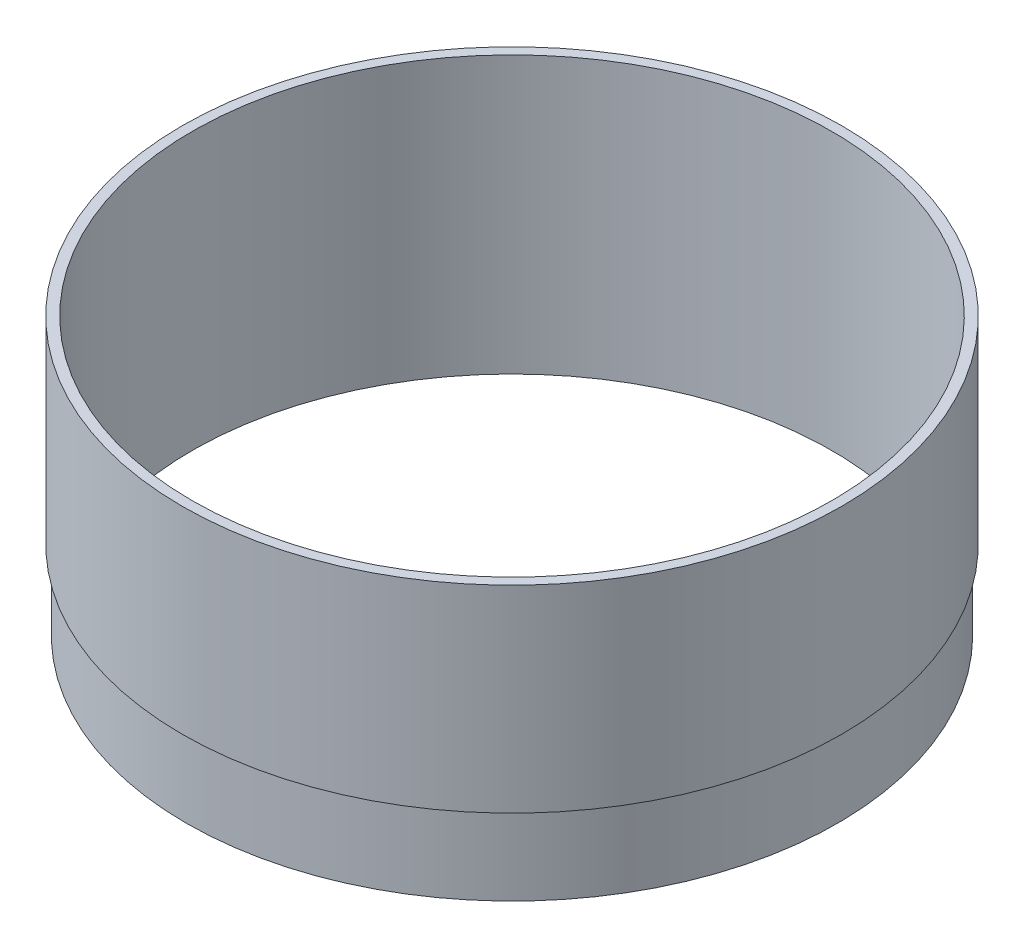
SolidWorks part; units mm, degrees
ref_plane "Front Plane" through (0, 0, 0) normal (0, 0, 1) x (1, 0, 0)
ref_plane "Top Plane" through (0, 0, 0) normal (0, 1, 0) x (1, 0, 0)
ref_plane "Right Plane" through (0, 0, 0) normal (1, 0, 0) x (0, 0, -1)
sketch "Sketch2" plane through (0, 0, 0) normal (0, 1, 0) x (1, 0, 0)
  circle A0 centre (0, 0) radius 16.5
  circle A1 centre (0, 0) radius 16.2
  dimension "D1" = 33
  dimension "D2" = 32.4
extrude "Boss-Extrude1" add sketch "Sketch2" along normal blind 4
sketch "Sketch3" plane through (0, 4, 0) normal (0, 1, 0) x (1, 0, 0)
  circle A0 centre (0, 0) radius 16.7
  circle A1 centre (0, 0) radius 16.2
  dimension "D1" = 33.4
  dimension "D2" = 32.4
extrude "Boss-Extrude2" add sketch "Sketch3" along normal blind 10
